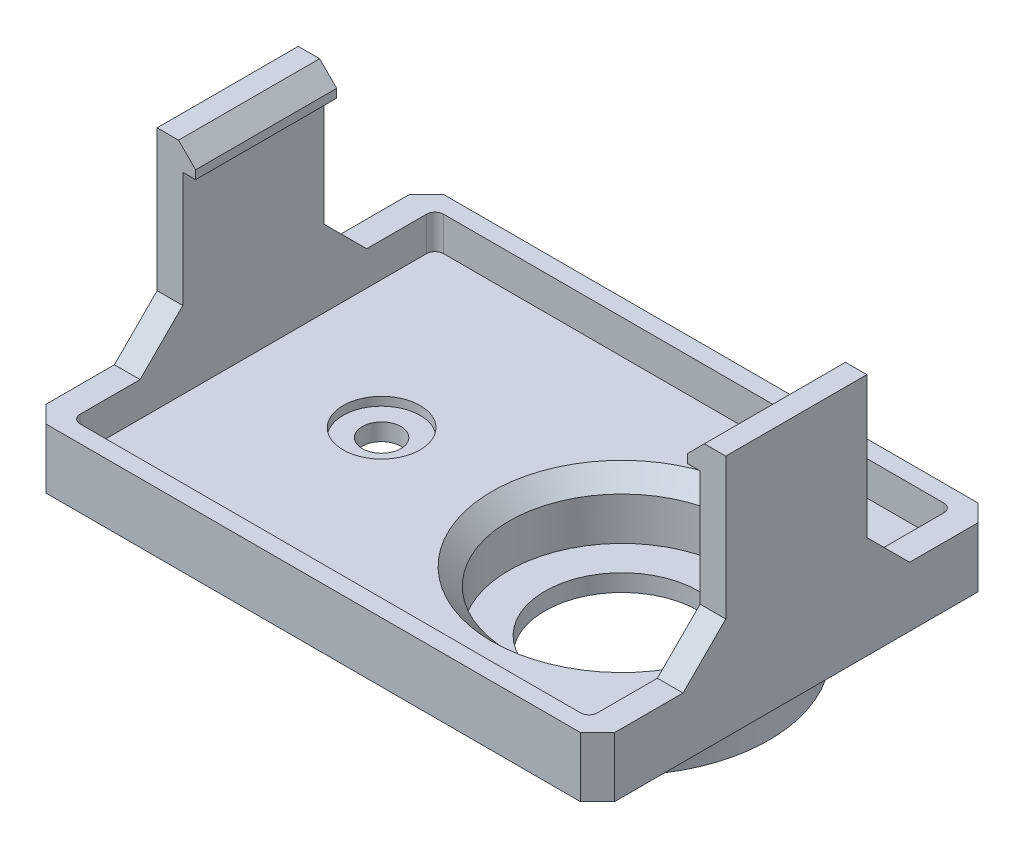
SolidWorks part; units mm, degrees
ref_plane "Front Plane" through (0, 0, 0) normal (0, 0, 1) x (1, 0, 0)
ref_plane "Top Plane" through (0, 0, 0) normal (0, 1, 0) x (1, 0, 0)
ref_plane "Right Plane" through (0, 0, 0) normal (1, 0, 0) x (0, 0, -1)
sketch "Sketch1" plane through (0, 0, 0) normal (0, 1, 0) x (1, 0, 0)
  line L1 (-33.1847, 18.5521) -> (33.3153, 18.5521)
  line L2 (-33.1847, 18.5521) -> (-33.1847, -27.9479)
  line L3 (-33.1847, -27.9479) -> (33.3153, -27.9479)
  line L4 (33.3153, 18.5521) -> (33.3153, -27.9479)
  dimension "D1" = 66.5
  dimension "D2" = 46.5
extrude "Boss-Extrude1" add sketch "Sketch1" along normal blind 3
sketch "Sketch2" plane through (0, 3, 0) normal (0, 1, 0) x (1, 0, 0)
  line L0 (33.3153, -27.9479) -> (33.3153, 18.5521) construction
  line L1 (-33.1847, 18.5521) -> (33.3153, 18.5521)
  line L2 (-33.1847, 18.5521) -> (-33.1847, 16.5521)
  line L3 (-30.1847, 16.5521) -> (30.3153, 16.5521)
  line L4 (33.3153, 18.5521) -> (33.3153, 16.5521)
  line L5 (-33.1847, 18.5521) -> (-33.1847, -27.9479) construction
  line L6 (-30.1847, -25.9479) -> (30.3153, -25.9479)
  line L7 (-33.1847, -25.9479) -> (-33.1847, -27.9479)
  line L8 (-33.1847, -27.9479) -> (33.3153, -27.9479)
  line L9 (33.3153, -25.9479) -> (33.3153, -27.9479)
  line L11 (-33.1847, 18.5521) -> (-30.1847, 18.5521)
  line L12 (-33.1847, 18.5521) -> (-33.1847, -27.9479)
  line L13 (-33.1847, -27.9479) -> (-30.1847, -27.9479)
  line L14 (-30.1847, 16.5521) -> (-30.1847, -25.9479)
  line L15 (33.3153, 18.5521) -> (30.3153, 18.5521)
  line L16 (33.3153, 18.5521) -> (33.3153, -27.9479)
  line L17 (33.3153, -27.9479) -> (30.3153, -27.9479)
  line L18 (30.3153, 16.5521) -> (30.3153, -25.9479)
  line M9 (-33.1847, 18.5521) -> (-33.1847, -27.9479)
  line M10 (-33.1847, -27.9479) -> (33.3153, -27.9479)
  line M11 (33.3153, -27.9479) -> (33.3153, 18.5521)
  line M12 (33.3153, 18.5521) -> (-33.1847, 18.5521)
  dimension "D1" = 2
  dimension "D2" = 2
  dimension "D3" = 3
  dimension "D4" = 3
extrude "Boss-Extrude2" add sketch "Sketch2" along normal blind 4 contours L1 L8 L3 L18 L6 L14 M12 M9 M10 M11
sketch "Sketch3" plane through (0, 3, 0) normal (0, 1, 0) x (1, 0, 0)
  line L0 (30.3153, 16.5521) -> (30.3153, -25.9479) construction
  circle A0 centre (12.9153, -4.6979) radius 13.2
  dimension "D1" = 26.4
  dimension "D2" = 17.4
extrude "Cut-Extrude1" cut sketch "Sketch3" against normal blind 4
sketch "Sketch4" plane through (0, 3, 0) normal (0, 1, 0) x (1, 0, 0)
  line L0 (-30.1847, 16.5521) -> (-30.1847, -25.9479) construction
  circle A0 centre (-15.1847, -4.6979) radius 2.25
  dimension "D1" = 4.5
  dimension "D2" = 15
extrude "Cut-Extrude2" cut sketch "Sketch4" against normal blind 4
sketch "Sketch5" plane through (0, 3, 0) normal (0, 1, 0) x (1, 0, 0)
  circle A0 centre (-15.1847, -4.6979) radius 4.5
  dimension "D1" = 9
extrude "Cut-Extrude3" cut sketch "Sketch5" against normal blind 1
sketch "Sketch6" plane through (0, 0, 0) normal (0, -1, 0) x (1, 0, 0)
  circle A0 centre (12.9153, 4.6979) radius 17.2
  circle A1 centre (12.9153, 4.6979) radius 13.2 construction
  circle A2 centre (12.9153, 4.6979) radius 13.2
  dimension "D1" = 4
extrude "Boss-Extrude3" add sketch "Sketch6" along normal blind 6
fillet "Fillet1" radius 1 4 edges at (-30.1847, 5, -16.5521) (30.3153, 5, -16.5521) (30.3153, 5, 25.9479) (-30.1847, 5, 25.9479)
chamfer "Chamfer1" distance 2 angle 45 4 edges at (33.3153, 3.5, -18.5521) (-33.1847, 3.5, -18.5521) (-33.1847, 3.5, 27.9479) (33.3153, 3.5, 27.9479)
sketch "Sketch7" plane through (0, 7, 0) normal (0, 1, 0) x (1, 0, 0)
  line L0 (33.3153, -25.9479) -> (33.3153, 16.5521) construction
  line L1 (33.3153, -12.9479) -> (30.3153, -12.9479)
  line L2 (33.3153, -12.9479) -> (33.3153, 3.5521)
  line L3 (33.3153, 3.5521) -> (30.3153, 3.5521)
  line L4 (30.3153, -12.9479) -> (30.3153, 3.5521)
  line L5 (30.3153, 15.5521) -> (30.3153, -24.9479) construction
  line L6 (-30.1847, 15.5521) -> (-30.1847, -24.9479) construction
  line L7 (-30.1847, -12.9479) -> (-33.1847, -12.9479)
  line L8 (-30.1847, -12.9479) -> (-30.1847, 3.5521)
  line L9 (-30.1847, 3.5521) -> (-33.1847, 3.5521)
  line L10 (-33.1847, -12.9479) -> (-33.1847, 3.5521)
  line L11 (-33.1847, 16.5521) -> (-33.1847, -25.9479) construction
  line L12 (-31.1847, -27.9479) -> (31.3153, -27.9479) construction
  line L13 (31.3153, 18.5521) -> (-31.1847, 18.5521) construction
  dimension "D1" = 15
  dimension "D2" = 15
  dimension "D3" = 15
  dimension "D4" = 15
extrude "Boss-Extrude4" add sketch "Sketch7" along normal blind 21.5
sketch "Sketch8" plane through (30.3153, 0, 0) normal (-1, 0, 0) x (0, 0, 1)
  line L0 (-3.5521, 28.5) -> (-3.5521, 7) construction
  line L1 (12.9479, 28.5) -> (-3.5521, 28.5)
  line L2 (12.9479, 28.5) -> (12.9479, 25.5)
  line L3 (12.9479, 25.5) -> (-3.5521, 25.5)
  line L4 (-3.5521, 28.5) -> (-3.5521, 25.5)
  dimension "D1" = 3
extrude "Boss-Extrude5" add sketch "Sketch8" along normal blind 1.5
sketch "Sketch9" plane through (-30.1847, 0, 0) normal (1, 0, 0) x (0, 0, -1)
  line L0 (3.5521, 28.5) -> (3.5521, 7) construction
  line L1 (-12.9479, 28.5) -> (3.5521, 28.5)
  line L2 (-12.9479, 28.5) -> (-12.9479, 25.5)
  line L3 (-12.9479, 25.5) -> (3.5521, 25.5)
  line L4 (3.5521, 28.5) -> (3.5521, 25.5)
  dimension "D1" = 3
extrude "Boss-Extrude6" add sketch "Sketch9" along normal blind 1.5
chamfer "Chamfer2" distance 2 angle 45 2 edges at (28.8153, 28.5, 4.6979) (-28.6847, 28.5, 4.6979)
chamfer "Chamfer3" distance 2 angle 45 1 edges at (12.9153, 3, 17.8979)
chamfer "Chamfer4" distance 2 angle 45 1 edges at (12.9153, 0, 21.8979)
chamfer "Chamfer5" distance 5 angle 45 2 edges at (31.8153, 7, -3.5521) (31.8153, 7, 12.9479)
chamfer "Chamfer6" distance 5 angle 45 2 edges at (-31.6847, 7, 12.9479) (-31.6847, 7, -3.5521)
sketch "Sketch10" plane through (0, -6, 0) normal (0, -1, 0) x (1, 0, 0)
  circle A0 centre (12.9153, 4.6979) radius 9
  circle A1 centre (12.9153, 4.6979) radius 13.2
  dimension "D1" = 18
extrude "Boss-Extrude7" add sketch "Sketch10" against normal blind 2
